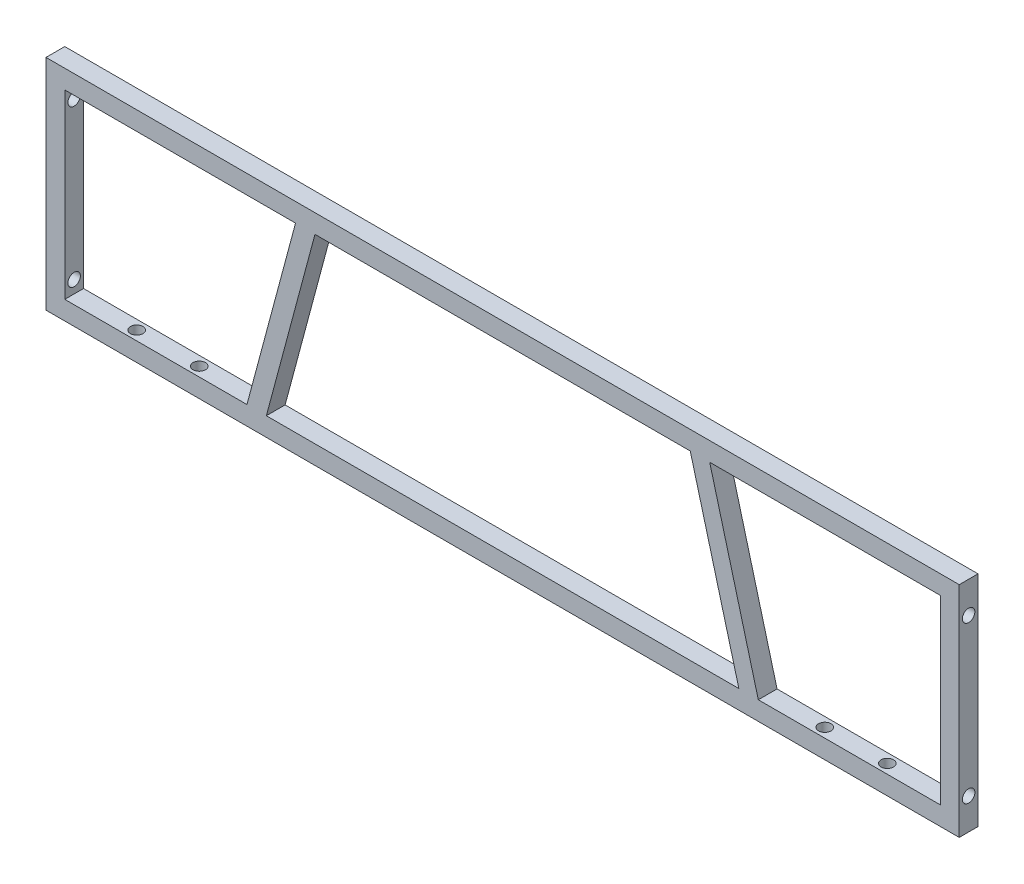
SolidWorks part; units mm, degrees
ref_plane "前视基准面" through (0, 0, 0) normal (0, 0, 1) x (1, 0, 0)
ref_plane "上视基准面" through (0, 0, 0) normal (0, 1, 0) x (1, 0, 0)
ref_plane "右视基准面" through (0, 0, 0) normal (1, 0, 0) x (0, 0, -1)
sketch "草图1" plane through (0, 0, 0) normal (0, 0, 1) x (1, 0, 0)
  line L1 (-146, -35) -> (146, -35)
  line L2 (-146, -35) -> (-146, 35)
  line L3 (-146, 35) -> (146, 35)
  line L4 (146, -35) -> (146, 35)
  line L5 (-146, -35) -> (146, 35) construction
  line L6 (-146, 35) -> (146, -35) construction
  line L7 (-140, -29) -> (140, -29)
  line L8 (-140, -29) -> (-140, 29)
  line L9 (-140, 29) -> (140, 29)
  line L10 (140, -29) -> (140, 29)
  line L11 (-140, -29) -> (140, 29) construction
  line L12 (-140, 29) -> (140, -29) construction
  point P0 (0, 0)
  point P6 (0, 0)
  dimension "D1" = 70
  dimension "D2" = 58
  dimension "D3" = 292
  dimension "D4" = 280
extrude "凸台-拉伸1" add sketch "草图1" along normal blind 6
sketch "草图2" plane through (0, 0, 0) normal (0, 0, 1) x (1, 0, 0)
  line L0 (0, -1000) -> (0, 49000) construction
  line L1 (-63.1058, 29) -> (-78.6469, -29) construction
  line L2 (140, 29) -> (-140, 29) construction
  line L3 (-140, -29) -> (140, -29) construction
  line L4 (-78.6469, -29) -> (-81.7527, -29)
  line L5 (-81.7527, -29) -> (-66.2117, 29)
  line L6 (-66.2117, 29) -> (-60, 29)
  line L7 (-60, 29) -> (-75.5411, -29)
  line L8 (-75.5411, -29) -> (-78.6469, -29)
  line L9 (75.5411, -29) -> (78.6469, -29)
  line L10 (60, 29) -> (75.5411, -29)
  line L11 (66.2117, 29) -> (60, 29)
  line L12 (81.7527, -29) -> (66.2117, 29)
  line L13 (78.6469, -29) -> (81.7527, -29)
  dimension "D1" = 75
  dimension "D2" = 3
  dimension "D3" = 3
  dimension "D4" = 60
extrude "凸台-拉伸2" add sketch "草图2" along normal blind 6
sketch "草图3" plane through (-146, 0, 0) normal (-1, 0, 0) x (0, 0, 1)
  line L0 (0, 35) -> (0, -35) construction
  circle A0 centre (3, 25) radius 2
  circle A1 centre (3, -25) radius 2
  dimension "D1" = 4
  dimension "D2" = 4
  dimension "D3" = 3
  dimension "D4" = 3
  dimension "D5" = 25
  dimension "D6" = 25
extrude "切除-拉伸1" cut sketch "草图3" against normal blind 6
ref_plane "基准面1" through (0, 0, 0) normal (1, 0, 0) x (0, 0, -1)
mirror "镜向1" about plane through (0, 0, 0) normal (1, 0, 0) of "切除-拉伸1"
sketch "草图4" plane through (0, -35, 0) normal (0, -1, 0) x (1, 0, 0)
  line L0 (0, -1000) -> (0, 49000) construction
  line L1 (-146, 0) -> (146, 0) construction
  circle A0 centre (-120, 3) radius 2
  circle A1 centre (-100, 3) radius 2
  circle A2 centre (120, 3) radius 2
  circle A3 centre (100, 3) radius 2
  dimension "D1" = 4
  dimension "D2" = 4
  dimension "D3" = 3
  dimension "D4" = 3
  dimension "D5" = 20
  dimension "D6" = 100
extrude "切除-拉伸2" cut sketch "草图4" against normal blind 6
